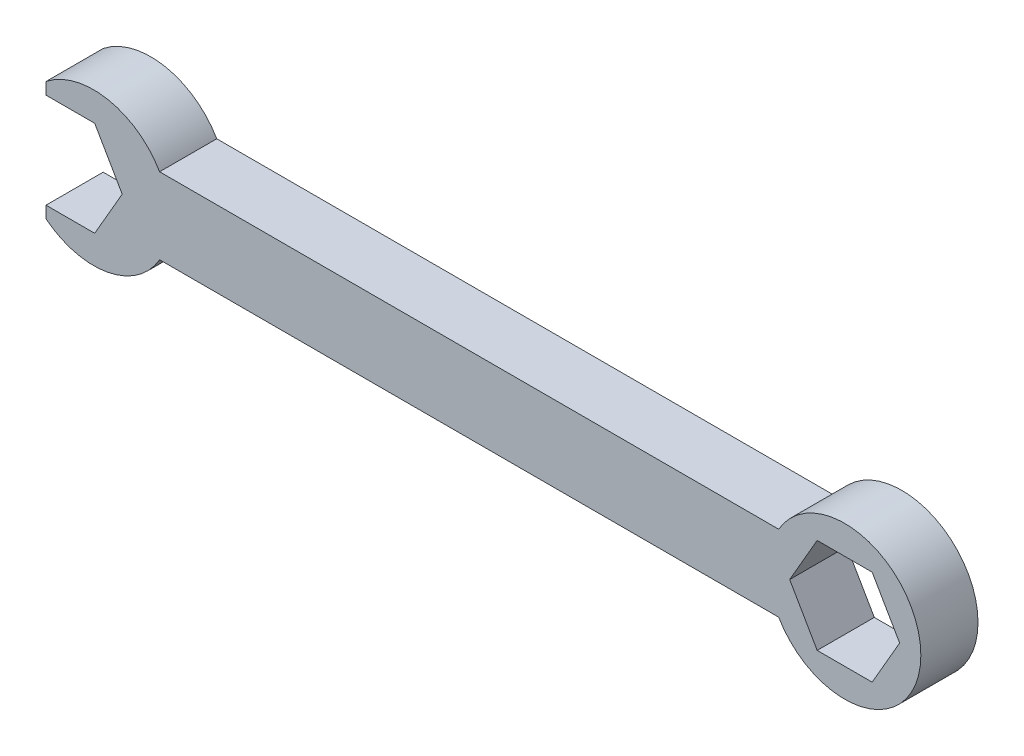
SolidWorks part; units mm, degrees
material "Cast Alloy Steel"
ref_plane "Front Plane" through (0, 0, 0) normal (0, 0, 1) x (1, 0, 0)
ref_plane "Top Plane" through (0, 0, 0) normal (0, 1, 0) x (1, 0, 0)
ref_plane "Right Plane" through (0, 0, 0) normal (1, 0, 0) x (0, 0, -1)
sketch "Sketch1" plane through (0, 0, 0) normal (0, 0, 1) x (1, 0, 0)
  line L0 (89.0053, 0) -> (0, 0) construction
  line L5 (4.9888, 5.08) -> (87.5388, 5.08)
  line L6 (-10.16, 7.9311) -> (-10.16, 6.35)
  line L7 (92.6715, 6.35) -> (100.0038, 6.35)
  line L8 (100.0038, 6.35) -> (103.67, 0)
  line L9 (103.67, 0) -> (100.0038, -6.35)
  line L10 (100.0038, -6.35) -> (92.6715, -6.35)
  line L11 (92.6715, -6.35) -> (89.0053, 0)
  line L12 (89.0053, 0) -> (92.6715, 6.35)
  line L13 (-10.16, 6.35) -> (-3.6662, 6.35)
  line L14 (-3.6662, 6.35) -> (0, 0)
  line L15 (106.4976, 0) -> (103.67, 0) construction
  line L16 (-3.6662, -6.35) -> (0, 0)
  line L17 (-10.16, -6.35) -> (-3.6662, -6.35)
  line L18 (-10.16, -7.9311) -> (-10.16, -6.35)
  line L19 (4.9888, -5.08) -> (87.5388, -5.08)
  circle A0 centre (96.3376, 0) radius 6.35 construction
  arc A1 (4.9888, -5.08) -> (-10.16, -7.9311) centre (-3.81, 0) cw
  arc A2 (87.5388, 5.08) -> (87.5388, -5.08) centre (96.3376, 0) cw
  arc A4 (4.9888, 5.08) -> (-10.16, 7.9311) centre (-3.81, 0) ccw
  dimension "D3" = 82.55
  dimension "D6" = 10.16
  dimension "D1" = 12.7
  dimension "D2" = 10.16
  dimension "D4" = 6.35
  dimension "D5" = 10.16
extrude "Boss-Extrude1" add sketch "Sketch1" along normal blind 7.62
